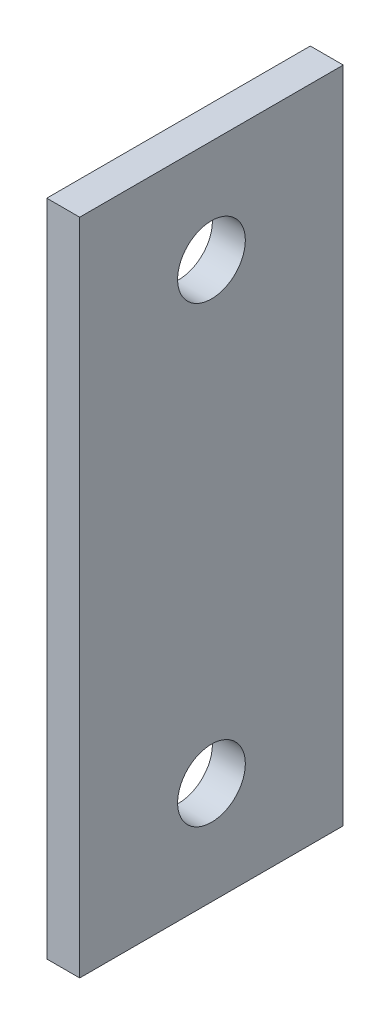
SolidWorks part; units mm, degrees
material "AISI 4130 Steel, annealed at 865C"
ref_plane "Front Plane" through (0, 0, 0) normal (0, 0, 1) x (1, 0, 0)
ref_plane "Top Plane" through (0, 0, 0) normal (0, 1, 0) x (1, 0, 0)
ref_plane "Right Plane" through (0, 0, 0) normal (1, 0, 0) x (0, 0, -1)
sketch "Sketch2" plane through (0, 0, 0) normal (1, 0, 0) x (0, 0, -1)
  line L0 (0, 21.844) -> (0, -21.844) construction
  line L1 (-12.7, -31.75) -> (12.7, -31.75)
  line L2 (-12.7, -31.75) -> (-12.7, 31.75)
  line L3 (-12.7, 31.75) -> (12.7, 31.75)
  line L4 (12.7, -31.75) -> (12.7, 31.75)
  line L5 (-12.7, -31.75) -> (12.7, 31.75) construction
  line L6 (-12.7, 31.75) -> (12.7, -31.75) construction
  circle A0 centre (0, 21.844) radius 3.2639
  circle A1 centre (0, -21.844) radius 3.2639
  point P0 (0, 0)
  point P6 (0, 0)
  point P7 (0, 0)
  dimension "D3" = 6.5278
  dimension "D4" = 6.5278
  dimension "D1" = 25.4
  dimension "D2" = 63.5
  dimension "D6" = 43.688
extrude "Boss-Extrude1" add sketch "Sketch2" along normal blind 3.175
